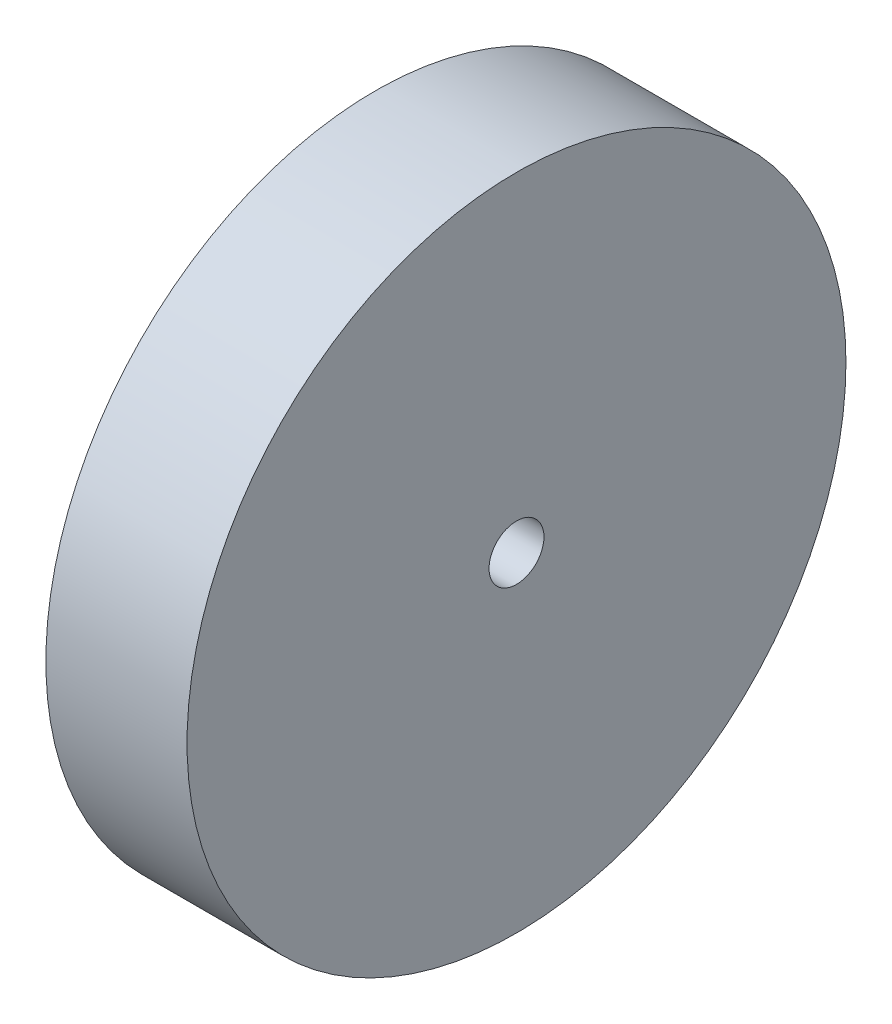
SolidWorks part; units mm, degrees
ref_plane "Front Plane" through (0, 0, 0) normal (0, 0, 1) x (1, 0, 0)
ref_plane "Top Plane" through (0, 0, 0) normal (0, 1, 0) x (1, 0, 0)
ref_plane "Right Plane" through (0, 0, 0) normal (1, 0, 0) x (0, 0, -1)
sketch "Sketch1" plane through (0, 0, 0) normal (1, 0, 0) x (0, 0, -1)
  circle A0 centre (0, 0) radius 35
  circle A1 centre (0, 0) radius 2.9167
  dimension "D1" = 70
extrude "Boss-Extrude1" add sketch "Sketch1" along normal blind 15
